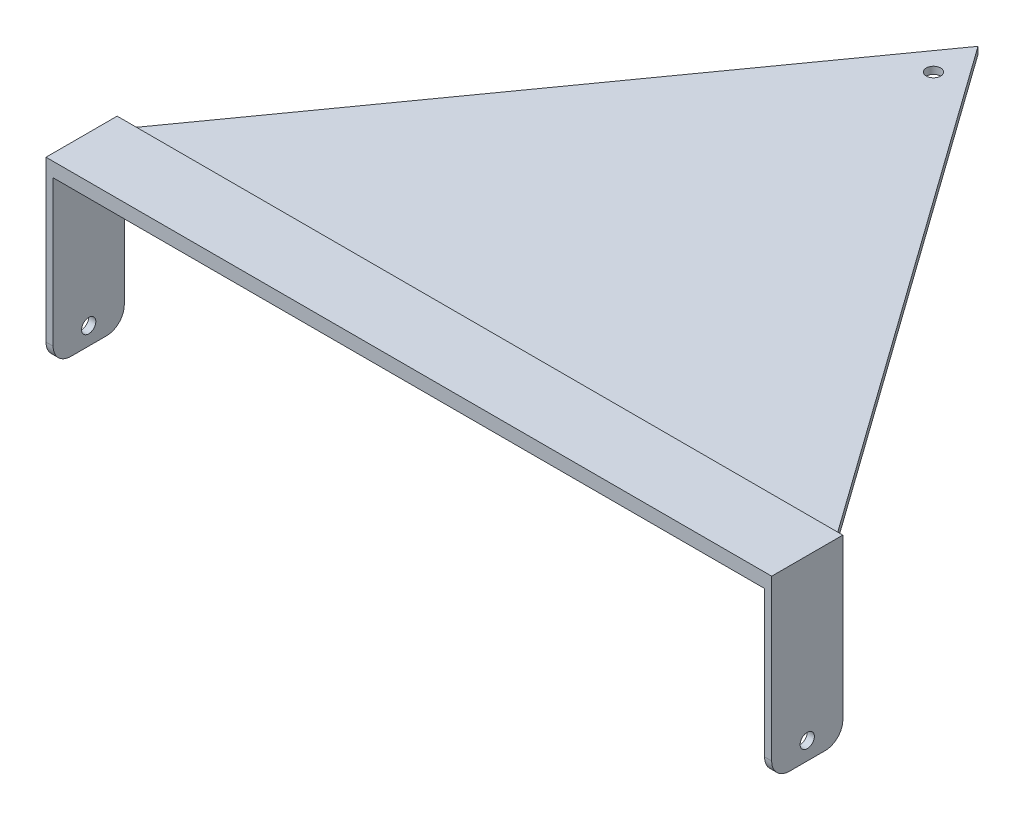
SolidWorks part; units mm, degrees
ref_plane "Front Plane" through (0, 0, 0) normal (0, 0, 1) x (1, 0, 0)
ref_plane "Top Plane" through (0, 0, 0) normal (0, 1, 0) x (1, 0, 0)
ref_plane "Right Plane" through (0, 0, 0) normal (1, 0, 0) x (0, 0, -1)
sketch "Sketch2" plane through (0, 0, 0) normal (0, 1, 0) x (1, 0, 0)
  line L3 (100, 158.6025) -> (100, 6.1073) construction
  line L4 (200, 0) -> (200, 10)
  line L5 (200, 10) -> (100, 150)
  line L6 (200, 0) -> (200, -10)
  line L7 (200, -10) -> (0, -10)
  line L8 (0, -10) -> (0, 0)
  line L9 (0, 10) -> (100, 150)
  line L10 (0, 0) -> (0, 10)
  circle A0 centre (100, 137.4773) radius 2
  point P3 (100, 137.4773)
  dimension "D5" = 10
  dimension "D1" = 200
  dimension "D2" = 170
  dimension "D3" = 170
  dimension "D6" = 10
  dimension "D7" = 10
  dimension "D8" = 10
extrude "Boss-Extrude1" add sketch "Sketch2" along normal blind 2
sketch "Sketch4" plane through (0, 2, 0) normal (0, 1, 0) x (1, 0, 0)
  line L1 (0, 10) -> (200, 10)
  line L2 (0, 10) -> (0, -10)
  line L3 (0, -10) -> (200, -10)
  line L4 (200, 10) -> (200, -10)
  line L5 (200, 10) -> (202, 10)
  line L6 (200, 10) -> (200, -10)
  line L7 (200, -10) -> (202, -10)
  line L8 (202, 10) -> (202, -10)
  line L9 (0, 10) -> (-2, 10)
  line L10 (0, 10) -> (0, -10)
  line L11 (0, -10) -> (-2, -10)
  line L12 (-2, 10) -> (-2, -10)
  line M3 (0, 10) -> (0, -10)
  line M4 (0, -10) -> (200, -10)
  line M5 (200, -10) -> (200, 10)
  dimension "D1" = 2
  dimension "D2" = 2
extrude "Boss-Extrude4" add sketch "Sketch4" along normal blind 2 contours L1 M3 M4 M5
sketch "Sketch7" plane through (0, 4, 0) normal (0, 1, 0) x (1, 0, 0)
  line L1 (0, 10) -> (-2, 10)
  line L2 (0, 10) -> (0, -10)
  line L3 (0, -10) -> (-2, -10)
  line L4 (-2, 10) -> (-2, -10)
  line L5 (200, 10) -> (202, 10)
  line L6 (200, 10) -> (200, -10)
  line L7 (200, -10) -> (202, -10)
  line L8 (202, 10) -> (202, -10)
  dimension "D1" = 2
  dimension "D2" = 2
  dimension "D3" = 20
  dimension "D4" = 20
extrude "Boss-Extrude5" add sketch "Sketch7" against normal blind 50
fillet "Fillet1" radius 5 4 edges at (201, -46, 10) (201, -46, -10) (-1, -46, -10) (-1, -46, 10)
sketch "Sketch9" plane through (-2, 0, 0) normal (-1, 0, 0) x (0, 0, 1)
  line L0 (10, -41) -> (10, 4) construction
  line L1 (-5, -46) -> (5, -46) construction
  circle A0 centre (0, -41) radius 2
  dimension "D1" = 4
  dimension "D2" = 10
  dimension "D3" = 5
extrude "Cut-Extrude1" cut sketch "Sketch9" against normal blind 250
equation "\"R\"= 150"
equation "\"d\"= 20"
